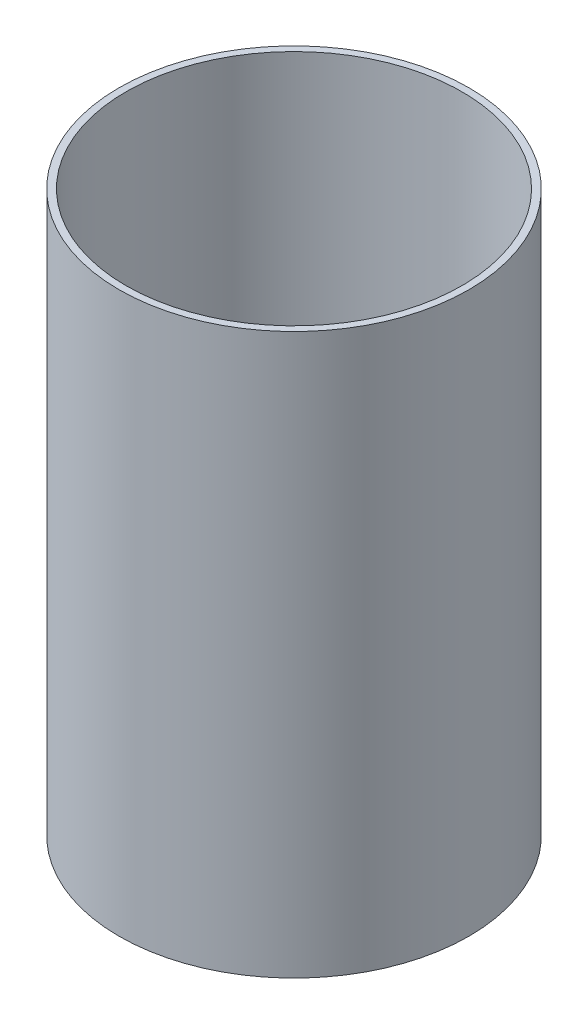
SolidWorks part; units mm, degrees
ref_plane "前视基准面" through (0, 0, 0) normal (0, 0, 1) x (1, 0, 0)
ref_plane "上视基准面" through (0, 0, 0) normal (0, 1, 0) x (1, 0, 0)
ref_plane "右视基准面" through (0, 0, 0) normal (1, 0, 0) x (0, 0, -1)
other "Configuration Table"
sketch "草图1" plane through (0, 0, 0) normal (0, 1, 0) x (1, 0, 0)
  circle A0 centre (0, 0) radius 39.6748
  circle A1 centre (0, 0) radius 38.1
  dimension "D1" = 79.3496
  dimension "D2" = 76.2
extrude "凸台-拉伸1" add sketch "草图1" along normal mid plane 127
equation "\"airframeInnerDiameter\"=3"
equation "\"outerDiameter\"=3.124"
equation "\"airframeBulkheadThickness\"=0.125"
equation "\"payloadAirframeLength\"=5"
equation "\"payloadCouplerInnerDiameter\"=2.88"
equation "\"payloadCouplerLength\"=5.5"
equation "\"payloadCouplerBandLength\"=1"
equation "\"payloadCouplerOuter\"=\"airframeInnerDiameter\""
equation "\"payloadCouplerOffsetFromAft\"=3"
equation "\"upperAirframeLength\"=12.5"
equation "\"recoveryBayInnerDiameter\"=2.88"
equation "\"recoveryBayLength\"=4"
equation "\"recoveryBandLength\"=1"
equation "\"recoveryCouplerOuter\"=\"airframeInnerDiameter\""
equation "\"recoveryOffsetFromAft\"=1.5"
equation "\"midAirframeLength\"=10"
equation "\"lowerAirframeLength\"=20"
equation "\"finSlotLength\"=4.1875"
equation "\"finSlotOffsetFromAft\"=1.5"
equation "\"finSlotWidth\"=0.125"
equation "\"D1@草图1\"=\"outerDiameter\""
equation "\"D2@草图1\"=\"airframeInnerDiameter\""
equation "\"D1@凸台-拉伸1\"=\"payloadAirframeLength\""
